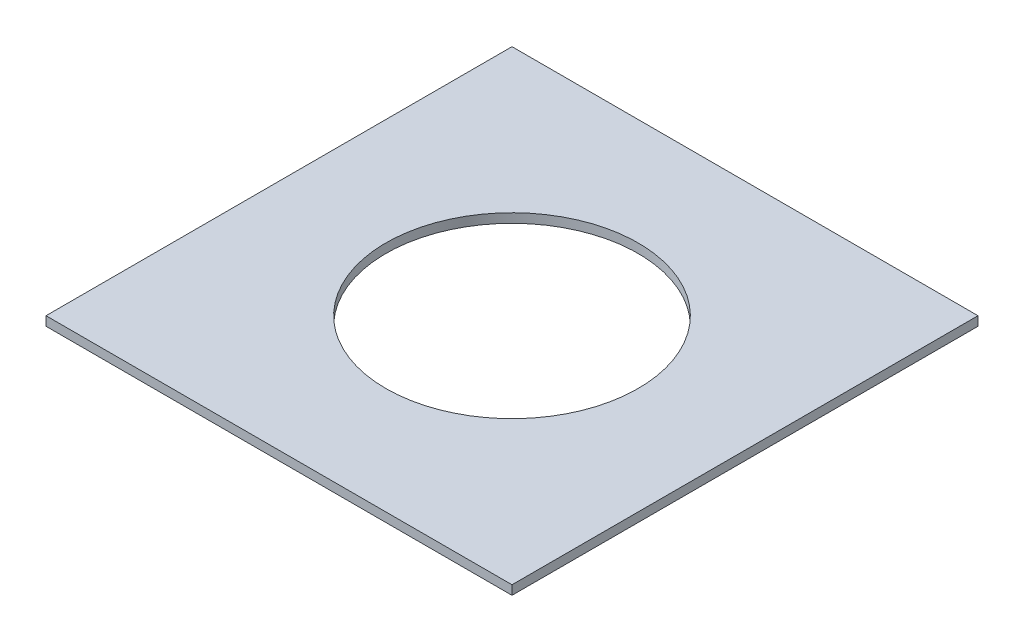
SolidWorks part; units mm, degrees
ref_plane "Front Plane" through (0, 0, 0) normal (0, 0, 1) x (1, 0, 0)
ref_plane "Top Plane" through (0, 0, 0) normal (0, 1, 0) x (1, 0, 0)
ref_plane "Right Plane" through (0, 0, 0) normal (1, 0, 0) x (0, 0, -1)
sketch "Sketch1" plane through (0, 0, 0) normal (0, 1, 0) x (1, 0, 0)
  line L1 (-50.8, 50.8) -> (50.8, 50.8)
  line L2 (-50.8, 50.8) -> (-50.8, -50.8)
  line L3 (-50.8, -50.8) -> (50.8, -50.8)
  line L4 (50.8, 50.8) -> (50.8, -50.8)
  line L5 (-50.8, 50.8) -> (50.8, -50.8) construction
  line L6 (-50.8, -50.8) -> (50.8, 50.8) construction
  circle A0 centre (0, 0) radius 27.5
  point P0 (0, 0)
  dimension "D2" = 55
  dimension "D1" = 101.6
extrude "Boss-Extrude1" add sketch "Sketch1" along normal blind 2
